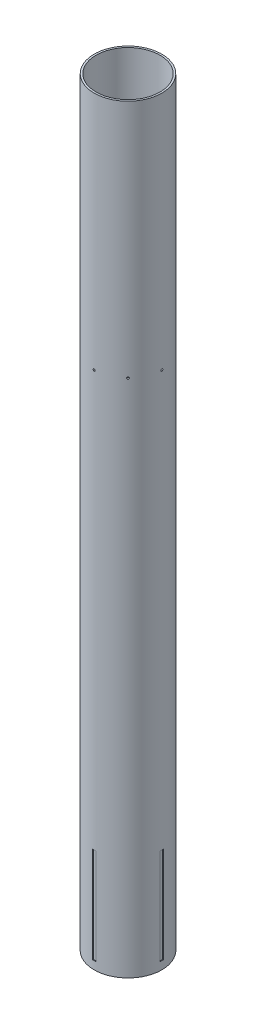
SolidWorks part; units mm, degrees
material "Hexcel AS4C (3000 Filaments)"
ref_plane "Front Plane" through (0, 0, 0) normal (0, 0, 1) x (1, 0, 0)
ref_plane "Top Plane" through (0, 0, 0) normal (0, 1, 0) x (1, 0, 0)
ref_plane "Right Plane" through (0, 0, 0) normal (1, 0, 0) x (0, 0, -1)
sketch "Sketch1" plane through (0, 0, 0) normal (0, 1, 0) x (1, 0, 0)
  circle A0 centre (0, 0) radius 50.8
  dimension "D1" = 101.6
extrude "Body Tube Extrusion" add sketch "Sketch1" along normal blind 1206.5 thin
ref_plane "Plane1" through (0, 0, 53.721) normal (0, 0, 1) x (1, 0, 0)
sketch "Sketch2" plane through (0, 0, 53.721) normal (0, 0, 1) x (1, 0, 0)
  line L0 (0, 1206.5) -> (0, 0) construction
  line L1 (50.8, 1206.5) -> (-50.8, 1206.5) construction
  line L2 (-53.721, 0) -> (53.721, 0) construction
  circle A0 centre (0, 825.5) radius 1.6383
  dimension "D1" = 3.2766
  dimension "D2" = 825.5
extrude "Bulkhead Hole" cut sketch "Sketch2" against normal up to next
pattern_circular "CirPattern1" count 8 over 360 about axis through (0, 1206.5, 0) along (0, -1, 0) of "Bulkhead Hole"
sketch "Sketch3" plane through (0, 0, 53.721) normal (0, 0, 1) x (1, 0, 0)
  line L0 (0, 0) -> (0, 12.7) construction
  line L1 (-50.8, 0) -> (50.8, 0) construction
  line L2 (0, 1206.5) -> (0, 0) construction
  line L4 (-2.667, 165.1) -> (2.667, 165.1)
  line L5 (-2.667, 165.1) -> (-2.667, 12.7)
  line L6 (-2.667, 12.7) -> (2.667, 12.7)
  line L7 (2.667, 165.1) -> (2.667, 12.7)
  point P10 (0, 12.7)
  dimension "D1" = 152.4
  dimension "D2" = 5.334
  dimension "D3" = 12.7
extrude "Cut-Extrude1" cut sketch "Sketch3" against normal blind 1.27
pattern_circular "CirPattern2" count 4 over 360 about axis through (0, 0, 0) along (0, 1, 0) of "Cut-Extrude1"
